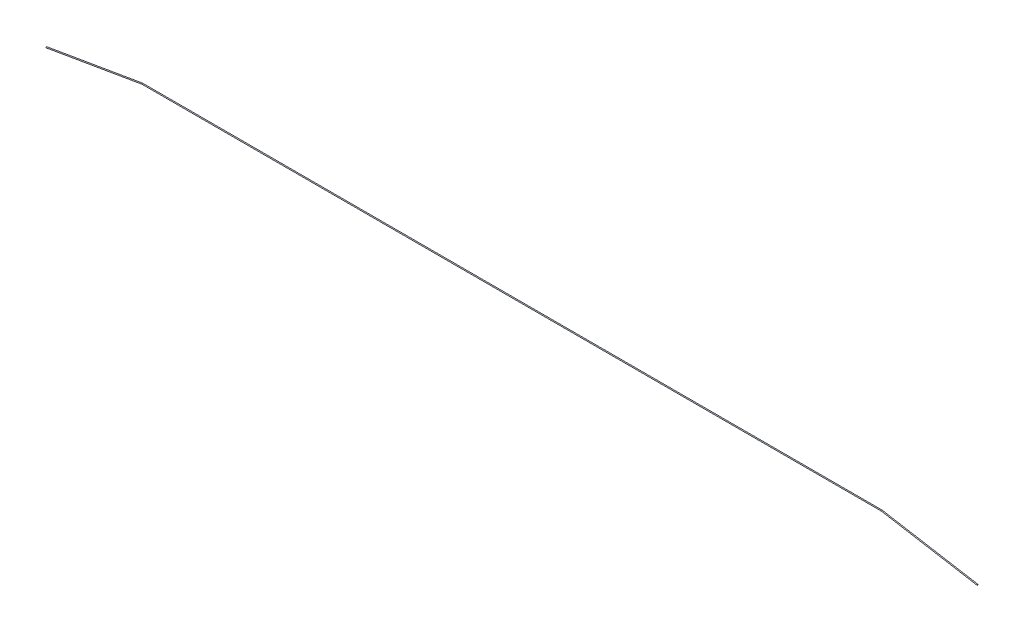
SolidWorks part; units mm, degrees
material "Plain Carbon Steel"
ref_plane "Front Plane" through (0, 0, 0) normal (0, 0, 1) x (1, 0, 0)
ref_plane "Top Plane" through (0, 0, 0) normal (0, 1, 0) x (1, 0, 0)
ref_plane "Right Plane" through (0, 0, 0) normal (1, 0, 0) x (0, 0, -1)
sketch "Sketch1" plane through (0, 0, 0) normal (0, 0, 1) x (1, 0, 0)
  line L0 (25.5905, 22.225) -> (20.32, 23.1253)
  line L2 (20.32, 23.1253) -> (-20.32, 23.1253)
  line L3 (-20.32, 23.1253) -> (-25.5905, 22.225)
  point P18 (-25.5905, 22.225)
  point P21 (-25.5905, 22.225)
  point P22 (25.5905, 22.225)
  point P23 (0, 0)
  point P24 (-20.32, 23.1253)
  point P25 (-20.32, 23.1253)
  point P26 (20.32, 23.1253)
sweep "Sweep1" add path "Sketch1" circular profile diameter 0.0508 parameters "D3"=0.0508
